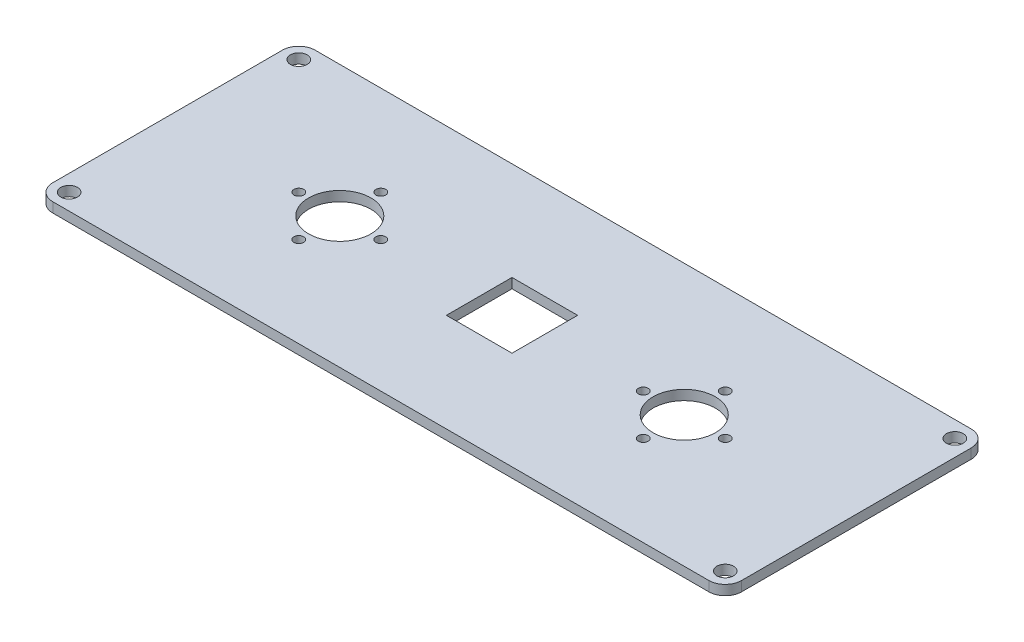
SolidWorks part; units mm, degrees
ref_plane "Front Plane" through (0, 0, 0) normal (0, 0, 1) x (1, 0, 0)
ref_plane "Top Plane" through (0, 0, 0) normal (0, 1, 0) x (1, 0, 0)
ref_plane "Right Plane" through (0, 0, 0) normal (1, 0, 0) x (0, 0, -1)
sketch "Sketch1" plane through (0, 0, 0) normal (0, 1, 0) x (1, 0, 0)
  line L0 (0, 40) -> (256.5691, 40) construction
  line L1 (0, 0) -> (210, 0)
  line L2 (0, 0) -> (0, 80)
  line L3 (0, 80) -> (210, 80)
  line L4 (210, 0) -> (210, 80)
  line L5 (95, 50) -> (115, 50)
  line L6 (95, 50) -> (95, 30)
  line L7 (95, 30) -> (115, 30)
  line L8 (115, 50) -> (115, 30)
  circle A0 centre (52.5, 40) radius 12.5 construction
  circle A1 centre (157.5, 40) radius 12.5 construction
  circle A2 centre (52.5, 52.5) radius 1.5
  circle A3 centre (65, 40) radius 1.5
  circle A4 centre (52.5, 27.5) radius 1.5
  circle A5 centre (40, 40) radius 1.5
  circle A6 centre (157.5, 52.5) radius 1.5
  circle A7 centre (170, 40) radius 1.5
  circle A8 centre (157.5, 27.5) radius 1.5
  circle A9 centre (145, 40) radius 1.5
  circle A10 centre (52.5, 40) radius 9.5
  circle A11 centre (157.5, 40) radius 9.5
  point P9 (105, 30)
  point P10 (105, 0)
  point P11 (0, 40)
  point P12 (95, 40)
  point P23 (5, 75)
  point P30 (52.5, 40)
  point P31 (205, 75)
  point P32 (205, 5)
  point P39 (157.5, 40)
  point P40 (5, 5)
  dimension "D5" = 25
  dimension "D7" = 25
  dimension "D9" = 3
  dimension "D16" = 19
  dimension "D17" = 19
  dimension "D1" = 80
  dimension "D2" = 210
  dimension "D3" = 20
  dimension "D4" = 20
  dimension "D6" = 52.5
  dimension "D8" = 52.5
  dimension "D12" = 5
  dimension "D13" = 5
  dimension "D14" = 5
  dimension "D15" = 5
  dimension "D10" = 4
  dimension "D11" = 4
extrude "Boss-Extrude1" add sketch "Sketch1" against normal blind 3
fillet "Fillet1" radius 5 4 edges at (0, -1.5, 0) (210, -1.5, 0) (210, -1.5, -80) (0, -1.5, -80)
hole_wizard "1/4-20 Tapped Hole1" positions "Sketch4" profile "Sketch5" tap size "1/4-20" standard "ANSI Inch" end condition through all
sketch "Sketch4" plane through (0, 0, 0) normal (0, 1, 0) x (1, 0, 0)
  line L0 (0, 75) -> (0, 5) construction
  line L1 (205, 80) -> (5, 80) construction
  line L2 (5, 0) -> (205, 0) construction
  line L3 (210, 5) -> (210, 75) construction
  point P0 (5, 75)
  point P2 (5, 5)
  point P5 (205, 5)
  point P7 (205, 75)
  point P14 (5, 5)
  point P15 (0, 0)
  point P18 (0, 0)
  point P21 (0, 0)
  dimension "D1" = 5
  dimension "D2" = 5
  dimension "D3" = 5
  dimension "D4" = 5
sketch "Sketch5" plane through (5, 0, -75) normal (1, 0, 0) x (0, 0, 1)
  line L0 (0, 0) -> (0, 3)
  line L1 (0, 3) -> (2.5527, 3)
  line L2 (2.5527, 3) -> (2.5527, 0)
  line L5 (2.5527, 0) -> (0, 0)
  line L11 (0, -6.35) -> (0, 107.95) construction
  dimension "Thru Tap Drill Dia." = 5.1054
  dimension "Thru Tap Drill Depth" = 3
cosmetic thread "Hole Thread1" parameters "D2"=6.35
cosmetic thread "Hole Thread2" parameters "D2"=6.35
cosmetic thread "Hole Thread3" parameters "D2"=6.35
cosmetic thread "Hole Thread4" parameters "D2"=6.35
